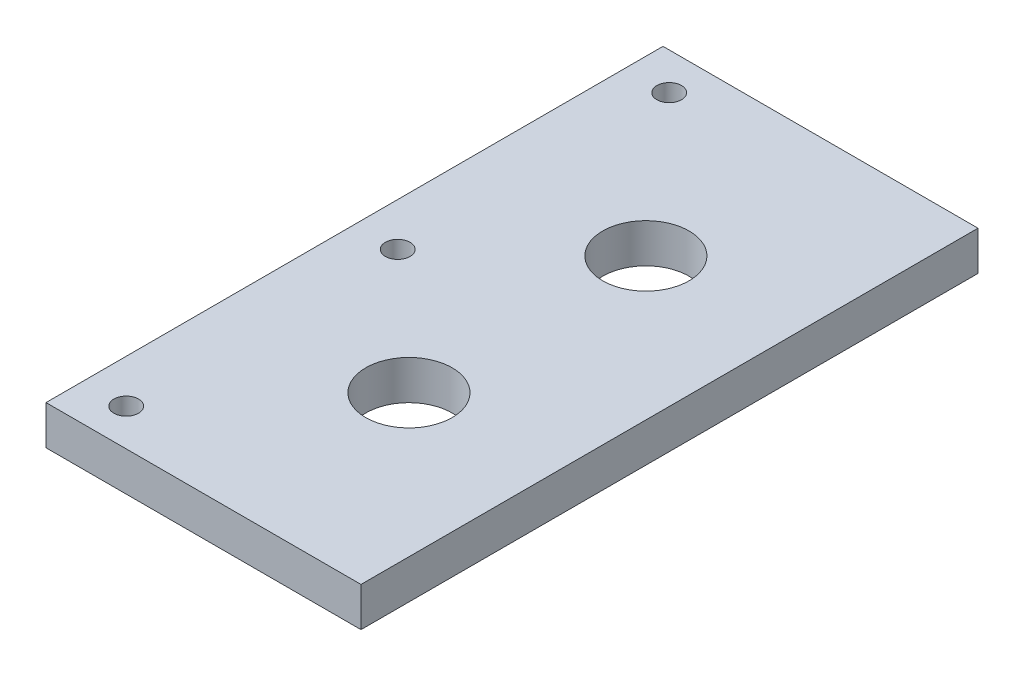
SolidWorks part; units mm, degrees
ref_plane "Front" through (0, 0, 0) normal (0, 0, 1) x (1, 0, 0)
ref_plane "Top" through (0, 0, 0) normal (0, 1, 0) x (1, 0, 0)
ref_plane "Right" through (0, 0, 0) normal (1, 0, 0) x (0, 0, -1)
sketch "Sketch1" plane through (0, 0, 0) normal (0, 1, 0) x (1, 0, 0)
  line L0 (0, 50) -> (46.0505, 50)
  line L1 (0, 0) -> (46.0505, 0)
  line L2 (0, 0) -> (0, 100)
  line L3 (0, 100) -> (46.0505, 100)
  line L4 (46.0505, 0) -> (46.0505, 100)
  line L5 (23.0253, 69.2) -> (23.0253, 30.8)
  line L6 (0, 100) -> (-5, 100)
  line L7 (-5, 100) -> (-5, 0)
  line L8 (-5, 0) -> (0, 0)
  line L12 (2, 50) -> (2, 94)
  line L13 (2, 50) -> (2, 6)
  circle A0 centre (23.0253, 69.2) radius 7
  circle A1 centre (23.0253, 30.8) radius 7
  circle A7 centre (2, 94) radius 2
  circle A8 centre (2, 6) radius 2
  circle A9 centre (2, 50) radius 2
  point P10 (23.0253, 50)
  dimension "D3" = 5
  dimension "D1" = 100
  dimension "D2" = 38.4
extrude "Boss-Extrude1" add sketch "Sketch1" along normal blind 6.35
